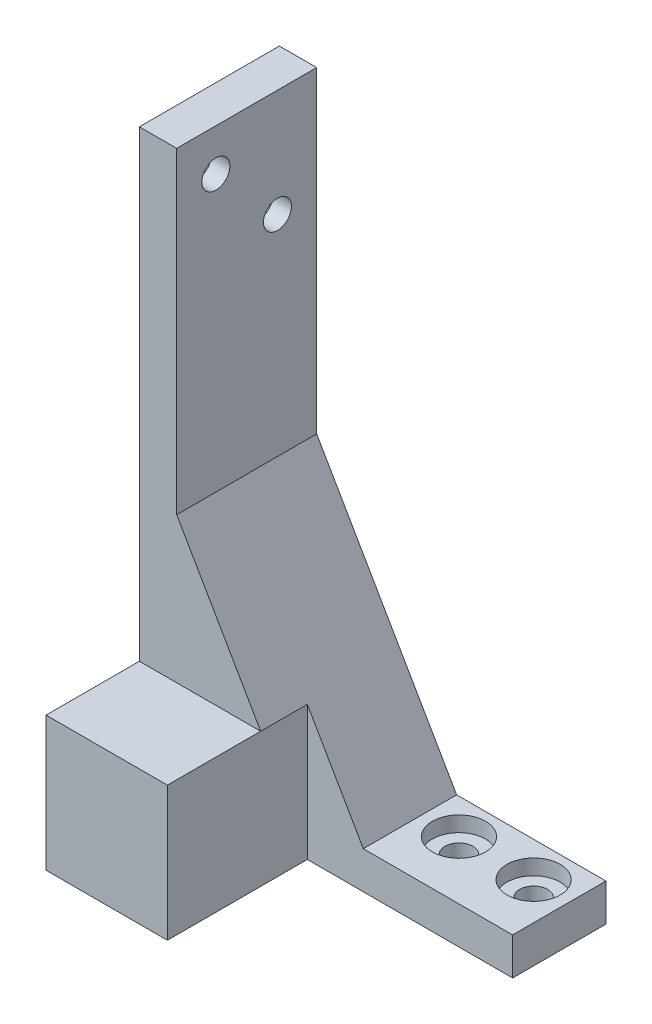
SolidWorks part; units mm, degrees
ref_plane "Alzado" through (0, 0, 0) normal (0, 0, 1) x (1, 0, 0)
ref_plane "Planta" through (0, 0, 0) normal (0, 1, 0) x (1, 0, 0)
ref_plane "Vista lateral" through (0, 0, 0) normal (1, 0, 0) x (0, 0, -1)
sketch "Croquis1" plane through (0, 0, 0) normal (0, 1, 0) x (1, 0, 0)
  line L1 (17.5, -7.5) -> (-17.5, -7.5)
  line L2 (17.5, -7.5) -> (17.5, 7.5)
  line L3 (17.5, 7.5) -> (-17.5, 7.5)
  line L4 (-17.5, -7.5) -> (-17.5, 7.5)
  line L5 (17.5, -7.5) -> (-17.5, 7.5) construction
  line L6 (17.5, 7.5) -> (-17.5, -7.5) construction
  circle A0 centre (5.5, 3.75) radius 1.5
  circle A1 centre (13.5, 3.75) radius 1.5
  point P0 (0, 0)
  dimension "D3" = 3.75
  dimension "D5" = 3
  dimension "D6" = 3
  dimension "D1" = 35
  dimension "D2" = 15
  dimension "D4" = 4
  dimension "D7" = 23
  dimension "D8" = 3.75
extrude "Saliente-Extruir1" add sketch "Croquis1" along normal blind 4
sketch "Croquis2" plane through (0, 4, 0) normal (0, 1, 0) x (1, 0, 0)
  line L0 (-17.5, -7.5) -> (17.5, -7.5) construction
  line L1 (-17.5, 7.5) -> (-13.5, 7.5)
  line L2 (-17.5, 7.5) -> (-17.5, -7.5)
  line L3 (-17.5, -7.5) -> (-13.5, -7.5)
  line L4 (-13.5, 7.5) -> (-13.5, -7.5)
  line L5 (-17.5, 7.5) -> (-13.5, -7.5) construction
  line L6 (-17.5, -7.5) -> (-13.5, 7.5) construction
  point P4 (-15.5, 0)
  dimension "D1" = 4
extrude "Saliente-Extruir2" add sketch "Croquis2" along normal blind 60
sketch "Croquis3" plane through (0, 0, 7.5) normal (0, 0, 1) x (1, 0, 0)
  line L3 (-13.5, 4) -> (-13.5, 30)
  line L4 (-13.5, 64) -> (-13.5, 4) construction
  line L6 (-13.5, 4) -> (1.5, 4)
  line L7 (-13.5, 4) -> (17.5, 4) construction
  line L8 (1.5, 4) -> (-13.5, 30)
  dimension "D1" = 30.0167
  dimension "D2" = 15
extrude "Saliente-Extruir3" add sketch "Croquis3" against normal up to surface (15 mm away) up to face at (-4.5, 22.6667, -7.5)
sketch "Croquis4" plane through (0, 4, 0) normal (0, 1, 0) x (1, 0, 0)
  circle A0 centre (5.5, 3.75) radius 2.85
  circle A1 centre (13.5, 3.75) radius 2.85
  dimension "D1" = 5.7
  dimension "D2" = 5.7
extrude "Cortar-Extruir1" cut sketch "Croquis4" against normal blind 1.65
sketch "Croquis5" plane through (17.5, 0, 0) normal (1, 0, 0) x (0, 0, -1)
  line L1 (-7.5, 0) -> (-2.5, 0)
  line L2 (-7.5, 0) -> (-7.5, 22)
  line L3 (-7.5, 22) -> (-2.5, 22)
  line L4 (-2.5, 0) -> (-2.5, 22)
  line L5 (-7.5, 0) -> (-2.5, 22) construction
  line L6 (-7.5, 22) -> (-2.5, 0) construction
  point P4 (-5, 11)
  dimension "D1" = 22
  dimension "D2" = 5
extrude "Cortar-Extruir2" cut sketch "Croquis5" against normal blind 22
sketch "Croquis6" plane through (-13.5, 0, 0) normal (1, 0, 0) x (0, 0, -1)
  line L0 (7.5, 64) -> (7.5, 30) construction
  line L1 (-7.5, 64) -> (7.5, 64)
  line L2 (-7.5, 64) -> (-7.5, 48)
  line L3 (-7.5, 48) -> (7.5, 48)
  line L4 (7.5, 64) -> (7.5, 48)
  line L5 (-7.5, 64) -> (7.5, 48) construction
  line L6 (-7.5, 48) -> (7.5, 64) construction
  circle A0 centre (-3.3, 59.52) radius 1.5
  circle A1 centre (3.3, 52.48) radius 1.5
  point P4 (0, 56)
  dimension "D2" = 3
  dimension "D3" = 3
  dimension "D1" = 16
  dimension "D4" = 4.2
  dimension "D5" = 4.2
extrude "Cortar-Extruir5" cut sketch "Croquis6" against normal up to next contours A0 | A1
sketch "Croquis7" plane through (-17.5, 0, 0) normal (-1, 0, 0) x (0, 0, 1)
  circle A0 centre (-3.3, 52.48) radius 2.5
  circle A1 centre (3.3, 59.52) radius 2.5
  dimension "D1" = 5
  dimension "D2" = 5
extrude "Cortar-Extruir6" cut sketch "Croquis7" against normal blind 2
sketch "Croquis9" plane through (0, 0, 7.5) normal (0, 0, 1) x (1, 0, 0)
  line L1 (-4.5, 14.4) -> (-17.5, 14.4)
  line L2 (-4.5, 14.4) -> (-4.5, 0)
  line L3 (-4.5, 0) -> (-17.5, 0)
  line L4 (-17.5, 14.4) -> (-17.5, 0)
  line L5 (-4.5, 14.4) -> (-17.5, 0) construction
  line L6 (-4.5, 0) -> (-17.5, 14.4) construction
  point P4 (-11, 7.2)
extrude "Saliente-Extruir4" add sketch "Croquis9" along normal blind 10
